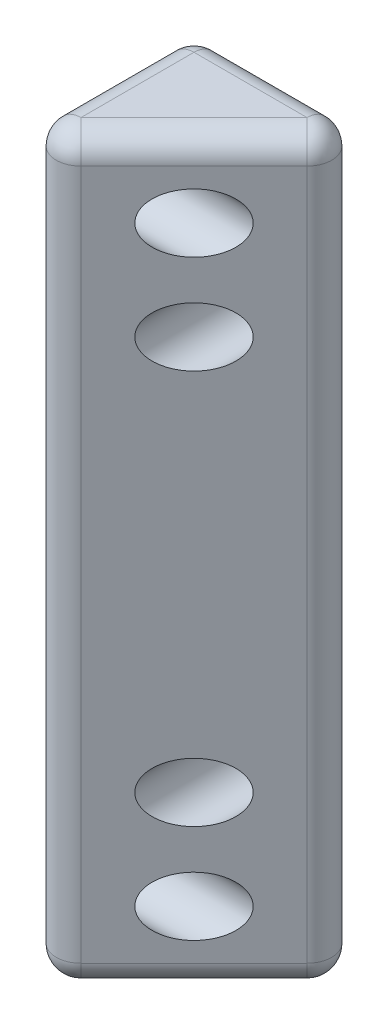
SolidWorks part; units mm, degrees
ref_plane "Front Plane" through (0, 0, 0) normal (0, 0, 1) x (1, 0, 0)
ref_plane "Top Plane" through (0, 0, 0) normal (0, 1, 0) x (1, 0, 0)
ref_plane "Right Plane" through (0, 0, 0) normal (1, 0, 0) x (0, 0, -1)
sketch "Sketch1" plane through (0, 0, 0) normal (0, 1, 0) x (1, 0, 0)
  line L0 (0, 0) -> (-12.7, 0)
  line L1 (-12.7, 0) -> (-12.7, -12.7)
  line L2 (-12.7, -12.7) -> (0, 0)
  dimension "D1" = 12.7
  dimension "D2" = 12.7
extrude "Boss-Extrude1" add sketch "Sketch1" along normal mid plane 47.625
sketch "Sketch2" plane through (-12.7, 0, 0) normal (-1, 0, 0) x (0, 0, 1)
  line L0 (6.35, -19.05) -> (6.35, 19.05) construction
  line L1 (0, 23.8125) -> (12.7, 23.8125) construction
  circle A0 centre (6.35, 19.05) radius 1.905
  circle A1 centre (6.35, -19.05) radius 1.905
  point P4 (6.35, 0)
  point P5 (6.9168, 19.05)
  point P9 (6.35, 23.8125)
  dimension "D1" = 3.81
  dimension "D2" = 38.1
extrude "Cut-Extrude1" cut sketch "Sketch2" against normal through all
sketch "Sketch3" plane through (0, 0, 0) normal (0, 0, -1) x (-1, 0, 0)
  line L0 (6.35, 12.7) -> (6.35, -12.7) construction
  line L1 (0, 23.8125) -> (12.7, 23.8125) construction
  circle A0 centre (6.35, -12.7) radius 1.905
  circle A1 centre (6.35, 12.7) radius 1.905
  point P4 (6.35, 0)
  point P8 (6.35, 23.8125)
  dimension "D1" = 25.4
  dimension "D2" = 3.81
extrude "Cut-Extrude2" cut sketch "Sketch3" against normal through all
fillet "Fillet1" radius 1.5875 9 edges at (-6.35, -23.8125, 0) (-12.7, -23.8125, 6.35) (-6.35, -23.8125, 6.35) (-12.7, 23.8125, 6.35) (-6.35, 23.8125, 0) (-6.35, 23.8125, 6.35) (0, 0, 0) (-12.7, 0, 0) (-12.7, 0, 12.7)
